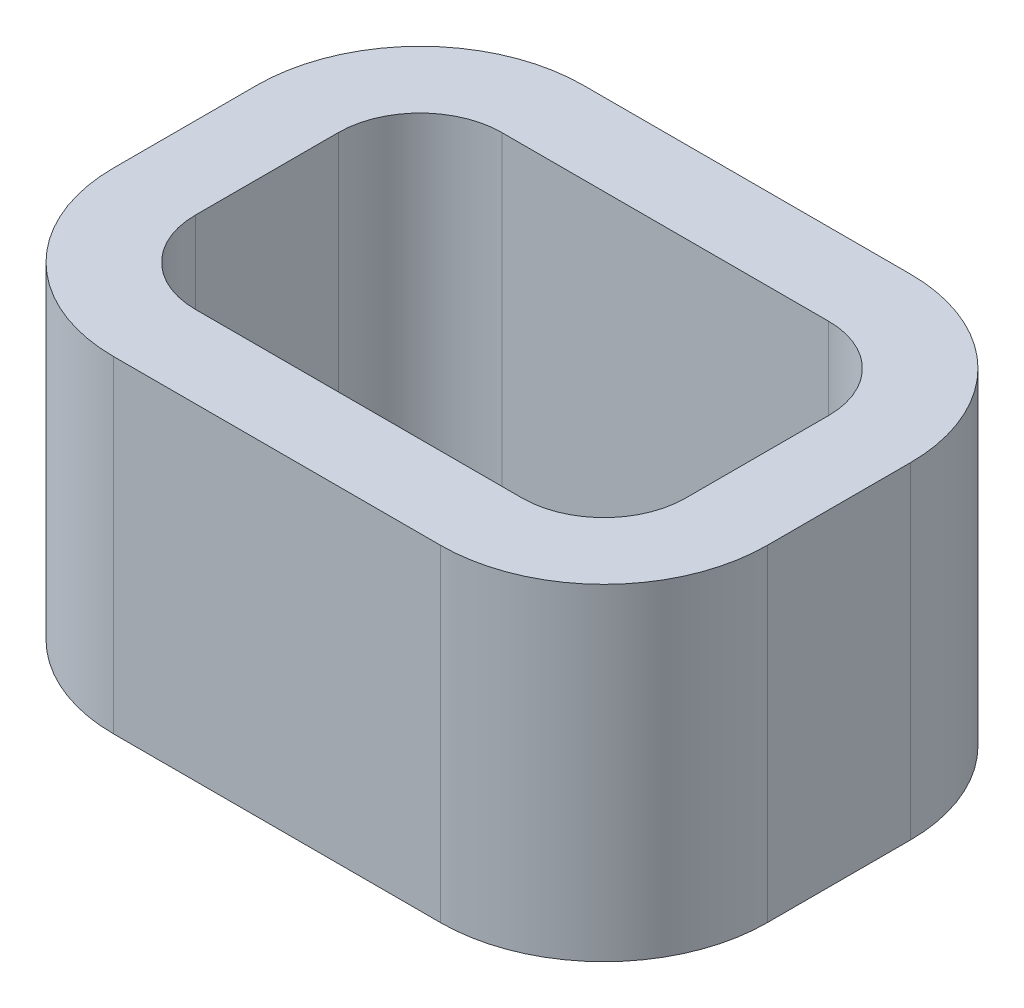
SolidWorks part; units mm, degrees
ref_plane "Front Plane" through (0, 0, 0) normal (0, 0, 1) x (1, 0, 0)
ref_plane "Top Plane" through (0, 0, 0) normal (0, 1, 0) x (1, 0, 0)
ref_plane "Right Plane" through (0, 0, 0) normal (1, 0, 0) x (0, 0, -1)
sketch "Sketch1" plane through (0, 0, 0) normal (0, 1, 0) x (1, 0, 0)
  line L0 (0, 0) -> (0.4, 0)
  line L1 (0.8, -0.4) -> (0.8, -0.75)
  line L2 (0.4, -1.15) -> (-0.4, -1.15)
  line L3 (-0.8, -0.75) -> (-0.8, -0.4)
  line L4 (-0.4, 0) -> (0, 0)
  arc A0 (0.4, -1.15) -> (0.8, -0.75) centre (0.4, -0.75) ccw
  arc A1 (0.8, -0.4) -> (0.4, 0) centre (0.4, -0.4) ccw
  arc A2 (-0.8, -0.4) -> (-0.4, 0) centre (-0.4, -0.4) cw
  arc A3 (-0.4, -1.15) -> (-0.8, -0.75) centre (-0.4, -0.75) cw
  point P8 (0.8, -1.15)
  point P11 (0.8, 0)
  point P14 (-0.8, 0)
  dimension "D3" = 0.4
  dimension "D1" = 1.6
  dimension "D2" = 1.15
extrude "Boss-Extrude1" add sketch "Sketch1" along normal blind 0.8
sketch "Sketch2" plane through (0, 0.8, 0) normal (0, 1, 0) x (1, 0, 0)
  line L0 (-0.4, -1.15) -> (0.4, -1.15) construction
  line L1 (-0.8, -0.4) -> (-0.8, -0.75) construction
  line L2 (0.8, -0.75) -> (0.8, -0.4) construction
  line L3 (0.4, 0) -> (-0.4, 0) construction
  line L4 (-0.4, -1.15) -> (0.4, -1.15) construction
  line L5 (-0.8, -0.4) -> (-0.8, -0.75) construction
  line L6 (0.8, -0.75) -> (0.8, -0.4) construction
  line L7 (0.4, 0) -> (-0.4, 0) construction
  line L9 (-0.4, -0.2) -> (0.4, -0.2)
  line L10 (-0.6, -0.4) -> (-0.6, -0.75)
  line L11 (-0.4, -0.95) -> (0.4, -0.95)
  line L12 (0.6, -0.4) -> (0.6, -0.75)
  arc A0 (0.4, -0.2) -> (0.6, -0.4) centre (0.4, -0.4) cw
  arc A1 (0.6, -0.75) -> (0.4, -0.95) centre (0.4, -0.75) cw
  arc A2 (-0.4, -0.95) -> (-0.6, -0.75) centre (-0.4, -0.75) cw
  arc A3 (-0.4, -0.2) -> (-0.6, -0.4) centre (-0.4, -0.4) ccw
  dimension "D5" = 0.2
  dimension "D1" = 0.2
  dimension "D2" = 0.2
  dimension "D3" = 0.2
  dimension "D4" = 0.2
extrude "Cut-Extrude1" cut sketch "Sketch2" against normal through all
